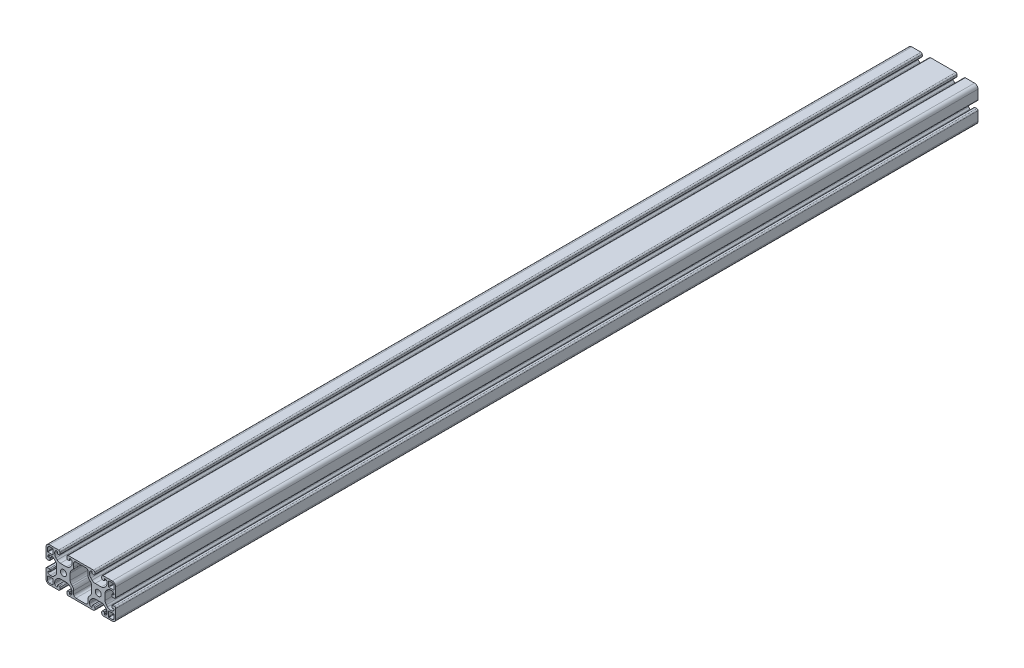
SolidWorks part; units mm, degrees
ref_plane "Plan de face" through (0, 0, 0) normal (0, 0, 1) x (1, 0, 0)
ref_plane "Plan de dessus" through (0, 0, 0) normal (0, 1, 0) x (1, 0, 0)
ref_plane "Plan de droite" through (0, 0, 0) normal (1, 0, 0) x (0, 0, -1)
ref_plane "Plan1" through (0, 0, 20) normal (0, 0, 1) x (1, 0, 0)
sketch "Esquisse1" plane through (0, 0, 20) normal (0, 0, 1) x (1, 0, 0)
  line L0 (66.5, 4.5) -> (65, 4.5)
  line L1 (64, 3.5) -> (64, 1.5)
  line L2 (65.5, 0) -> (76, 0)
  line L3 (80, 4) -> (80, 14.5)
  line L4 (78.5, 16) -> (76.5, 16)
  line L5 (75.5, 15) -> (75.5, 13.5)
  line L6 (76, 13) -> (77.5, 13)
  line L7 (75.5, 10) -> (74.1924, 10)
  line L8 (70.6569, 11.4645) -> (69.2145, 12.9069)
  line L9 (67.75, 16.4424) -> (67.75, 23.5576)
  line L10 (69.2145, 27.0931) -> (70.6569, 28.5355)
  line L11 (74.1924, 30) -> (75.5, 30)
  line L12 (77.5, 27) -> (76, 27)
  line L13 (75.5, 26.5) -> (75.5, 25)
  line L14 (76.5, 24) -> (78.5, 24)
  line L15 (80, 25.5) -> (80, 36)
  line L16 (76, 40) -> (65.5, 40)
  line L17 (64, 38.5) -> (64, 36.5)
  line L18 (65, 35.5) -> (66.5, 35.5)
  line L19 (67, 36) -> (67, 37.5)
  line L20 (70, 35.5) -> (70, 34.1924)
  line L21 (68.5355, 30.6569) -> (67.0931, 29.2145)
  line L22 (63.5576, 27.75) -> (56.4424, 27.75)
  line L23 (52.9069, 29.2145) -> (51.4645, 30.6569)
  line L24 (50, 34.1924) -> (50, 35.5)
  line L25 (53, 37.5) -> (53, 36)
  line L26 (53.5, 35.5) -> (55, 35.5)
  line L27 (56, 36.5) -> (56, 38.5)
  line L28 (54.5, 40) -> (25.5, 40)
  line L29 (24, 38.5) -> (24, 36.5)
  line L30 (25, 35.5) -> (26.5, 35.5)
  line L31 (27, 36) -> (27, 37.5)
  line L32 (30, 35.5) -> (30, 34.1924)
  line L33 (28.5355, 30.6569) -> (27.0931, 29.2145)
  line L34 (23.5576, 27.75) -> (16.4424, 27.75)
  line L35 (12.9069, 29.2145) -> (11.4645, 30.6569)
  line L36 (10, 34.1924) -> (10, 35.5)
  line L37 (13, 37.5) -> (13, 36)
  line L38 (13.5, 35.5) -> (15, 35.5)
  line L39 (16, 36.5) -> (16, 38.5)
  line L40 (14.5, 40) -> (4, 40)
  line L41 (0, 36) -> (0, 25.5)
  line L42 (1.5, 24) -> (3.5, 24)
  line L43 (4.5, 25) -> (4.5, 26.5)
  line L44 (4, 27) -> (2.5, 27)
  line L45 (4.5, 30) -> (5.8076, 30)
  line L46 (9.3431, 28.5355) -> (10.7855, 27.0931)
  line L47 (12.25, 23.5576) -> (12.25, 16.4424)
  line L48 (10.7855, 12.9069) -> (9.3431, 11.4645)
  line L49 (5.8076, 10) -> (4.5, 10)
  line L50 (2.5, 13) -> (4, 13)
  line L51 (4.5, 13.5) -> (4.5, 15)
  line L52 (3.5, 16) -> (1.5, 16)
  line L53 (0, 14.5) -> (0, 4)
  line L54 (4, 0) -> (14.5, 0)
  line L55 (16, 1.5) -> (16, 3.5)
  line L56 (15, 4.5) -> (13.5, 4.5)
  line L57 (13, 4) -> (13, 2.5)
  line L58 (10, 4.5) -> (10, 5.8076)
  line L59 (11.4645, 9.3431) -> (12.9069, 10.7855)
  line L60 (16.4424, 12.25) -> (23.5576, 12.25)
  line L61 (27.0931, 10.7855) -> (28.5355, 9.3431)
  line L62 (30, 5.8076) -> (30, 4.5)
  line L63 (27, 2.5) -> (27, 4)
  line L64 (26.5, 4.5) -> (25, 4.5)
  line L65 (24, 3.5) -> (24, 1.5)
  line L66 (25.5, 0) -> (54.5, 0)
  line L67 (56, 1.5) -> (56, 3.5)
  line L68 (55, 4.5) -> (53.5, 4.5)
  line L69 (53, 4) -> (53, 2.5)
  line L70 (50, 4.5) -> (50, 5.8076)
  line L71 (51.4645, 9.3431) -> (52.9069, 10.7855)
  line L72 (56.4424, 12.25) -> (63.5576, 12.25)
  line L73 (67.0931, 10.7855) -> (68.5355, 9.3431)
  line L74 (70, 5.8076) -> (70, 4.5)
  line L75 (67, 2.5) -> (67, 4)
  line L76 (31.8, 4.5) -> (31.8, 8.2503)
  line L77 (30.3355, 11.7858) -> (29.2145, 12.9069)
  line L78 (27.75, 16.4424) -> (27.75, 23.5576)
  line L79 (29.2145, 27.0931) -> (30.3355, 28.2142)
  line L80 (31.8, 31.7497) -> (31.8, 35.5)
  line L81 (34.3, 38) -> (45.7, 38)
  line L82 (48.2, 35.5) -> (48.2, 31.7497)
  line L83 (49.6645, 28.2142) -> (50.7855, 27.0931)
  line L84 (52.25, 23.5576) -> (52.25, 16.4424)
  line L85 (50.7855, 12.9069) -> (49.6645, 11.7858)
  line L86 (48.2, 8.2503) -> (48.2, 4.5)
  line L87 (45.7, 2) -> (34.3, 2)
  line L88 (7.7, 1.8) -> (4, 1.8)
  line L89 (1.8, 4) -> (1.8, 7.7)
  line L90 (2.3, 8.2) -> (7.7, 8.2)
  line L91 (8.2, 7.7) -> (8.2, 2.3)
  line L92 (72.3, 38.2) -> (76, 38.2)
  line L93 (78.2, 36) -> (78.2, 32.3)
  line L94 (77.7, 31.8) -> (72.3, 31.8)
  line L95 (71.8, 32.3) -> (71.8, 37.7)
  line L96 (78.2, 7.7) -> (78.2, 4)
  line L97 (76, 1.8) -> (72.3, 1.8)
  line L98 (71.8, 2.3) -> (71.8, 7.7)
  line L99 (72.3, 8.2) -> (77.7, 8.2)
  line L100 (1.8, 32.3) -> (1.8, 36)
  line L101 (4, 38.2) -> (7.7, 38.2)
  line L102 (8.2, 37.7) -> (8.2, 32.3)
  line L103 (7.7, 31.8) -> (2.3, 31.8)
  arc A0 (67, 4) -> (66.5, 4.5) centre (66.5, 4) ccw
  arc A1 (65, 4.5) -> (64, 3.5) centre (65, 3.5) ccw
  arc A2 (64, 1.5) -> (65.5, 0) centre (65.5, 1.5) ccw
  arc A3 (76, 0) -> (80, 4) centre (76, 4) ccw
  arc A4 (80, 14.5) -> (78.5, 16) centre (78.5, 14.5) ccw
  arc A5 (76.5, 16) -> (75.5, 15) centre (76.5, 15) ccw
  arc A6 (75.5, 13.5) -> (76, 13) centre (76, 13.5) ccw
  arc A7 (77.5, 13) -> (78, 12.5) centre (77.5, 12.5) cw
  arc A8 (78, 12.5) -> (75.5, 10) centre (75.5, 12.5) cw
  arc A9 (74.1924, 10) -> (70.6569, 11.4645) centre (74.1924, 15) cw
  arc A10 (69.2145, 12.9069) -> (67.75, 16.4424) centre (72.75, 16.4424) cw
  arc A11 (67.75, 23.5576) -> (69.2145, 27.0931) centre (72.75, 23.5576) cw
  arc A12 (70.6569, 28.5355) -> (74.1924, 30) centre (74.1924, 25) cw
  arc A13 (75.5, 30) -> (78, 27.5) centre (75.5, 27.5) cw
  arc A14 (78, 27.5) -> (77.5, 27) centre (77.5, 27.5) cw
  arc A15 (76, 27) -> (75.5, 26.5) centre (76, 26.5) ccw
  arc A16 (75.5, 25) -> (76.5, 24) centre (76.5, 25) ccw
  arc A17 (78.5, 24) -> (80, 25.5) centre (78.5, 25.5) ccw
  arc A18 (80, 36) -> (76, 40) centre (76, 36) ccw
  arc A19 (65.5, 40) -> (64, 38.5) centre (65.5, 38.5) ccw
  arc A20 (64, 36.5) -> (65, 35.5) centre (65, 36.5) ccw
  arc A21 (66.5, 35.5) -> (67, 36) centre (66.5, 36) ccw
  arc A22 (67, 37.5) -> (67.5, 38) centre (67.5, 37.5) cw
  arc A23 (67.5, 38) -> (70, 35.5) centre (67.5, 35.5) cw
  arc A24 (70, 34.1924) -> (68.5355, 30.6569) centre (65, 34.1924) cw
  arc A25 (67.0931, 29.2145) -> (63.5576, 27.75) centre (63.5576, 32.75) cw
  arc A26 (56.4424, 27.75) -> (52.9069, 29.2145) centre (56.4424, 32.75) cw
  arc A27 (51.4645, 30.6569) -> (50, 34.1924) centre (55, 34.1924) cw
  arc A28 (50, 35.5) -> (52.5, 38) centre (52.5, 35.5) cw
  arc A29 (52.5, 38) -> (53, 37.5) centre (52.5, 37.5) cw
  arc A30 (53, 36) -> (53.5, 35.5) centre (53.5, 36) ccw
  arc A31 (55, 35.5) -> (56, 36.5) centre (55, 36.5) ccw
  arc A32 (56, 38.5) -> (54.5, 40) centre (54.5, 38.5) ccw
  arc A33 (25.5, 40) -> (24, 38.5) centre (25.5, 38.5) ccw
  arc A34 (24, 36.5) -> (25, 35.5) centre (25, 36.5) ccw
  arc A35 (26.5, 35.5) -> (27, 36) centre (26.5, 36) ccw
  arc A36 (27, 37.5) -> (27.5, 38) centre (27.5, 37.5) cw
  arc A37 (27.5, 38) -> (30, 35.5) centre (27.5, 35.5) cw
  arc A38 (30, 34.1924) -> (28.5355, 30.6569) centre (25, 34.1924) cw
  arc A39 (27.0931, 29.2145) -> (23.5576, 27.75) centre (23.5576, 32.75) cw
  arc A40 (16.4424, 27.75) -> (12.9069, 29.2145) centre (16.4424, 32.75) cw
  arc A41 (11.4645, 30.6569) -> (10, 34.1924) centre (15, 34.1924) cw
  arc A42 (10, 35.5) -> (12.5, 38) centre (12.5, 35.5) cw
  arc A43 (12.5, 38) -> (13, 37.5) centre (12.5, 37.5) cw
  arc A44 (13, 36) -> (13.5, 35.5) centre (13.5, 36) ccw
  arc A45 (15, 35.5) -> (16, 36.5) centre (15, 36.5) ccw
  arc A46 (16, 38.5) -> (14.5, 40) centre (14.5, 38.5) ccw
  arc A47 (4, 40) -> (0, 36) centre (4, 36) ccw
  arc A48 (0, 25.5) -> (1.5, 24) centre (1.5, 25.5) ccw
  arc A49 (3.5, 24) -> (4.5, 25) centre (3.5, 25) ccw
  arc A50 (4.5, 26.5) -> (4, 27) centre (4, 26.5) ccw
  arc A51 (2.5, 27) -> (2, 27.5) centre (2.5, 27.5) cw
  arc A52 (2, 27.5) -> (4.5, 30) centre (4.5, 27.5) cw
  arc A53 (5.8076, 30) -> (9.3431, 28.5355) centre (5.8076, 25) cw
  arc A54 (10.7855, 27.0931) -> (12.25, 23.5576) centre (7.25, 23.5576) cw
  arc A55 (12.25, 16.4424) -> (10.7855, 12.9069) centre (7.25, 16.4424) cw
  arc A56 (9.3431, 11.4645) -> (5.8076, 10) centre (5.8076, 15) cw
  arc A57 (4.5, 10) -> (2, 12.5) centre (4.5, 12.5) cw
  arc A58 (2, 12.5) -> (2.5, 13) centre (2.5, 12.5) cw
  arc A59 (4, 13) -> (4.5, 13.5) centre (4, 13.5) ccw
  arc A60 (4.5, 15) -> (3.5, 16) centre (3.5, 15) ccw
  arc A61 (1.5, 16) -> (0, 14.5) centre (1.5, 14.5) ccw
  arc A62 (0, 4) -> (4, 0) centre (4, 4) ccw
  arc A63 (14.5, 0) -> (16, 1.5) centre (14.5, 1.5) ccw
  arc A64 (16, 3.5) -> (15, 4.5) centre (15, 3.5) ccw
  arc A65 (13.5, 4.5) -> (13, 4) centre (13.5, 4) ccw
  arc A66 (13, 2.5) -> (12.5, 2) centre (12.5, 2.5) cw
  arc A67 (12.5, 2) -> (10, 4.5) centre (12.5, 4.5) cw
  arc A68 (10, 5.8076) -> (11.4645, 9.3431) centre (15, 5.8076) cw
  arc A69 (12.9069, 10.7855) -> (16.4424, 12.25) centre (16.4424, 7.25) cw
  arc A70 (23.5576, 12.25) -> (27.0931, 10.7855) centre (23.5576, 7.25) cw
  arc A71 (28.5355, 9.3431) -> (30, 5.8076) centre (25, 5.8076) cw
  arc A72 (30, 4.5) -> (27.5, 2) centre (27.5, 4.5) cw
  arc A73 (27.5, 2) -> (27, 2.5) centre (27.5, 2.5) cw
  arc A74 (27, 4) -> (26.5, 4.5) centre (26.5, 4) ccw
  arc A75 (25, 4.5) -> (24, 3.5) centre (25, 3.5) ccw
  arc A76 (24, 1.5) -> (25.5, 0) centre (25.5, 1.5) ccw
  arc A77 (54.5, 0) -> (56, 1.5) centre (54.5, 1.5) ccw
  arc A78 (56, 3.5) -> (55, 4.5) centre (55, 3.5) ccw
  arc A79 (53.5, 4.5) -> (53, 4) centre (53.5, 4) ccw
  arc A80 (53, 2.5) -> (52.5, 2) centre (52.5, 2.5) cw
  arc A81 (52.5, 2) -> (50, 4.5) centre (52.5, 4.5) cw
  arc A82 (50, 5.8076) -> (51.4645, 9.3431) centre (55, 5.8076) cw
  arc A83 (52.9069, 10.7855) -> (56.4424, 12.25) centre (56.4424, 7.25) cw
  arc A84 (63.5576, 12.25) -> (67.0931, 10.7855) centre (63.5576, 7.25) cw
  arc A85 (68.5355, 9.3431) -> (70, 5.8076) centre (65, 5.8076) cw
  arc A86 (70, 4.5) -> (67.5, 2) centre (67.5, 4.5) cw
  arc A87 (67.5, 2) -> (67, 2.5) centre (67.5, 2.5) cw
  circle A88 centre (20, 20) radius 3.4
  circle A89 centre (60, 20) radius 3.4
  arc A90 (34.3, 2) -> (31.8, 4.5) centre (34.3, 4.5) cw
  arc A91 (31.8, 8.2503) -> (30.3355, 11.7858) centre (26.8, 8.2503) ccw
  arc A92 (29.2145, 12.9069) -> (27.75, 16.4424) centre (32.75, 16.4424) cw
  arc A93 (27.75, 23.5576) -> (29.2145, 27.0931) centre (32.75, 23.5576) cw
  arc A94 (30.3355, 28.2142) -> (31.8, 31.7497) centre (26.8, 31.7497) ccw
  arc A95 (31.8, 35.5) -> (34.3, 38) centre (34.3, 35.5) cw
  arc A96 (45.7, 38) -> (48.2, 35.5) centre (45.7, 35.5) cw
  arc A97 (48.2, 31.7497) -> (49.6645, 28.2142) centre (53.2, 31.7497) ccw
  arc A98 (50.7855, 27.0931) -> (52.25, 23.5576) centre (47.25, 23.5576) cw
  arc A99 (52.25, 16.4424) -> (50.7855, 12.9069) centre (47.25, 16.4424) cw
  arc A100 (49.6645, 11.7858) -> (48.2, 8.2503) centre (53.2, 8.2503) ccw
  arc A101 (48.2, 4.5) -> (45.7, 2) centre (45.7, 4.5) cw
  arc A102 (8.2, 2.3) -> (7.7, 1.8) centre (7.7, 2.3) cw
  arc A103 (4, 1.8) -> (1.8, 4) centre (4, 4) cw
  arc A104 (1.8, 7.7) -> (2.3, 8.2) centre (2.3, 7.7) cw
  arc A105 (7.7, 8.2) -> (8.2, 7.7) centre (7.7, 7.7) cw
  arc A106 (71.8, 37.7) -> (72.3, 38.2) centre (72.3, 37.7) cw
  arc A107 (76, 38.2) -> (78.2, 36) centre (76, 36) cw
  arc A108 (78.2, 32.3) -> (77.7, 31.8) centre (77.7, 32.3) cw
  arc A109 (72.3, 31.8) -> (71.8, 32.3) centre (72.3, 32.3) cw
  arc A110 (77.7, 8.2) -> (78.2, 7.7) centre (77.7, 7.7) cw
  arc A111 (78.2, 4) -> (76, 1.8) centre (76, 4) cw
  arc A112 (72.3, 1.8) -> (71.8, 2.3) centre (72.3, 2.3) cw
  arc A113 (71.8, 7.7) -> (72.3, 8.2) centre (72.3, 7.7) cw
  arc A114 (2.3, 31.8) -> (1.8, 32.3) centre (2.3, 32.3) cw
  arc A115 (1.8, 36) -> (4, 38.2) centre (4, 36) cw
  arc A116 (7.7, 38.2) -> (8.2, 37.7) centre (7.7, 37.7) cw
  arc A117 (8.2, 32.3) -> (7.7, 31.8) centre (7.7, 32.3) cw
extrude "Boss.-Extru.1" add sketch "Esquisse1" against normal blind 990
